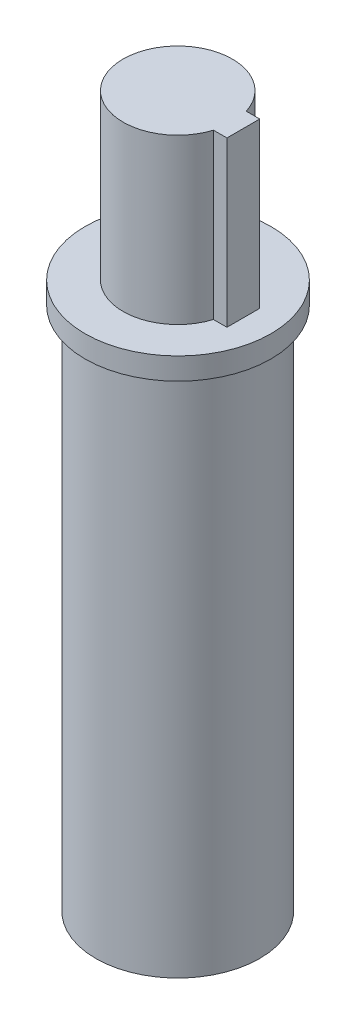
SolidWorks part; units mm, degrees
ref_plane "Front Plane" through (0, 0, 0) normal (0, 0, 1) x (1, 0, 0)
ref_plane "Top Plane" through (0, 0, 0) normal (0, 1, 0) x (1, 0, 0)
ref_plane "Right Plane" through (0, 0, 0) normal (1, 0, 0) x (0, 0, -1)
sketch "Sketch1" plane through (0, 0, 0) normal (0, 1, 0) x (1, 0, 0)
  line L0 (4.7697, -1.5) -> (6, -1.5)
  line L1 (5, 0) -> (6, 0) construction
  line L3 (4.7697, 1.5) -> (6, 1.5)
  line L4 (6, -1.5) -> (6, 1.5)
  arc A0 (4.7697, 1.5) -> (4.7697, -1.5) centre (0, 0) ccw
  dimension "D1" = 10
  dimension "D2" = 1.5
extrude "Boss-Extrude1" add sketch "Sketch1" along normal blind 15 contours A0 L0 L4 L3
sketch "Sketch2" plane through (0, 0, 0) normal (0, -1, 0) x (1, 0, 0)
  circle A0 centre (0, 0) radius 7.5
  dimension "D1" = 15
extrude "Boss-Extrude2" add sketch "Sketch2" along normal blind 50
scale "Scale1" scale about centroid uniform scaling yes scale factor 10
sketch "Sketch3" plane through (0, 189.3462, 0) normal (0, 1, 0) x (1, 0, 0)
  circle A0 centre (0, 0) radius 85
  dimension "D1" = 170
extrude "Boss-Extrude3" add sketch "Sketch3" against normal blind 20
